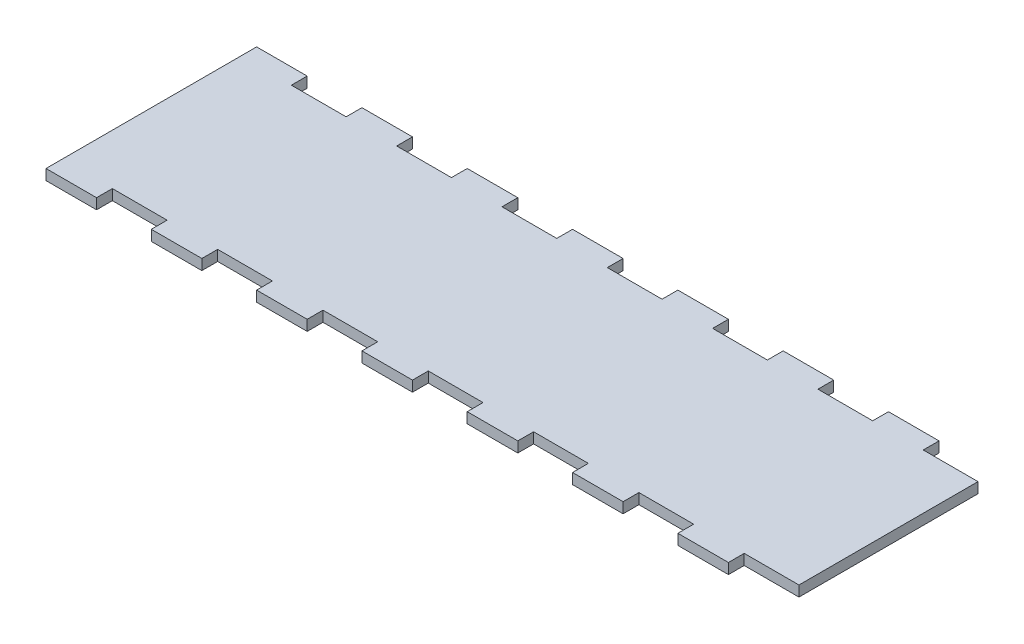
SolidWorks part; units mm, degrees
ref_plane "Front Plane" through (0, 0, 0) normal (0, 0, 1) x (1, 0, 0)
ref_plane "Top Plane" through (0, 0, 0) normal (0, 1, 0) x (1, 0, 0)
ref_plane "Right Plane" through (0, 0, 0) normal (1, 0, 0) x (0, 0, -1)
sketch "Sketch1" plane through (0, 0, 0) normal (0, 1, 0) x (1, 0, 0)
  line L1 (-88.9, -21.59) -> (88.9, -21.59)
  line L2 (-88.9, -21.59) -> (-88.9, 21.59)
  line L3 (-88.9, 21.59) -> (88.9, 21.59)
  line L4 (88.9, -21.59) -> (88.9, 21.59)
  line L5 (-88.9, -21.59) -> (88.9, 21.59) construction
  line L6 (-88.9, 21.59) -> (88.9, -21.59) construction
  point P0 (0, 0)
  dimension "D1" = 177.8
  dimension "D2" = 43.18
extrude "Boss-Extrude1" add sketch "Sketch1" along normal blind 2.54
sketch "Sketch2" plane through (0, 0, 0) normal (0, 1, 0) x (1, 0, 0)
  line L0 (-63.5, 25.4) -> (-51.308, 25.4)
  line L1 (-88.9, 21.59) -> (-76.708, 21.59)
  line L2 (-88.9, 21.59) -> (-88.9, 25.4)
  line L3 (-88.9, 25.4) -> (-76.708, 25.4)
  line L4 (-76.708, 21.59) -> (-76.708, 25.4)
  line L5 (-63.5, 21.59) -> (-63.5, 25.4)
  line L6 (-63.5, 21.59) -> (-51.308, 21.59)
  line L7 (-51.308, 21.59) -> (-51.308, 25.4)
  line L8 (-38.1, 25.4) -> (-25.908, 25.4)
  line L9 (-38.1, 21.59) -> (-38.1, 25.4)
  line L10 (-38.1, 21.59) -> (-25.908, 21.59)
  line L11 (-25.908, 21.59) -> (-25.908, 25.4)
  line L12 (-12.7, 25.4) -> (-0.508, 25.4)
  line L13 (-12.7, 21.59) -> (-12.7, 25.4)
  line L14 (-12.7, 21.59) -> (-0.508, 21.59)
  line L15 (-0.508, 21.59) -> (-0.508, 25.4)
  line L16 (12.7, 25.4) -> (24.892, 25.4)
  line L17 (12.7, 21.59) -> (12.7, 25.4)
  line L18 (12.7, 21.59) -> (24.892, 21.59)
  line L19 (24.892, 21.59) -> (24.892, 25.4)
  line L20 (38.1, 25.4) -> (50.292, 25.4)
  line L21 (38.1, 21.59) -> (38.1, 25.4)
  line L22 (38.1, 21.59) -> (50.292, 21.59)
  line L23 (50.292, 21.59) -> (50.292, 25.4)
  line L24 (63.5, 25.4) -> (75.692, 25.4)
  line L25 (63.5, 21.59) -> (63.5, 25.4)
  line L26 (63.5, 21.59) -> (75.692, 21.59)
  line L27 (75.692, 21.59) -> (75.692, 25.4)
  dimension "D1" = 12.192
  dimension "D2" = 3.81
  dimension "D3" = 7
extrude "Boss-Extrude2" add sketch "Sketch2" along normal blind 2.54
mirror "Mirror1" about plane through (0, 0, 0) normal (0, 0, 1) of "Boss-Extrude2"
